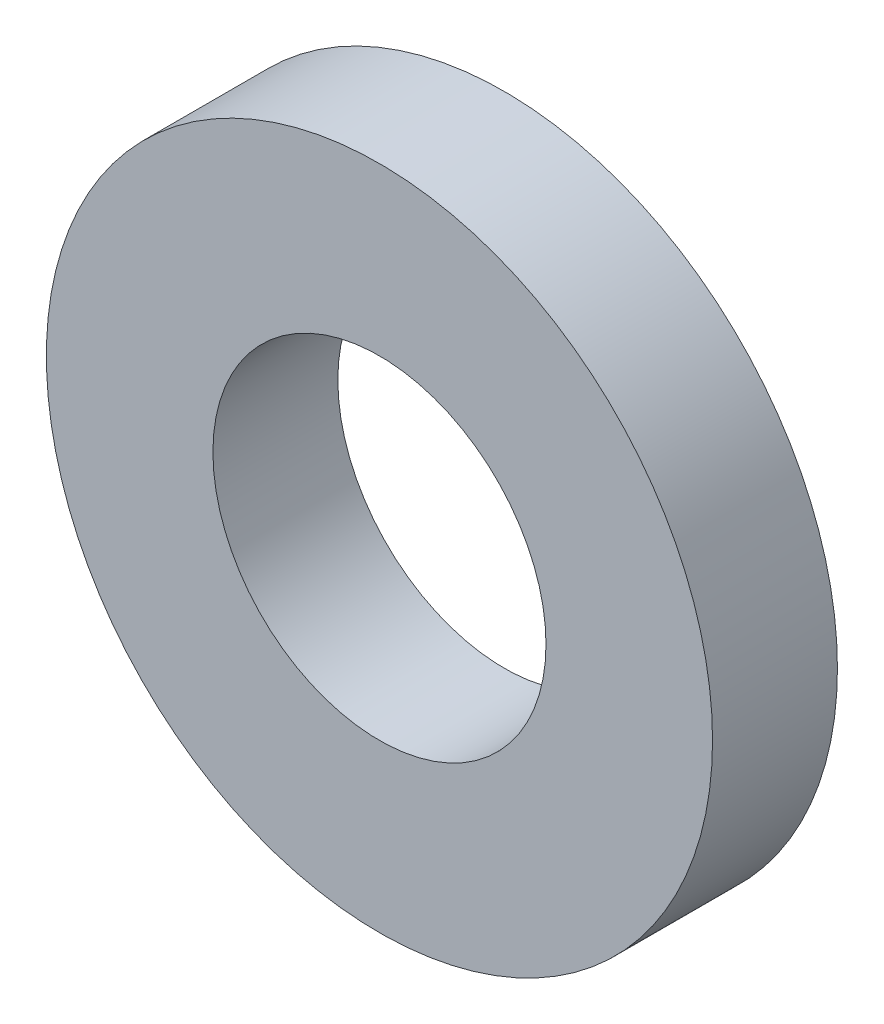
SolidWorks part; units mm, degrees
material "Nylon 101"
ref_plane "Front Plane" through (0, 0, 0) normal (0, 0, 1) x (1, 0, 0)
ref_plane "Top Plane" through (0, 0, 0) normal (0, 1, 0) x (1, 0, 0)
ref_plane "Right Plane" through (0, 0, 0) normal (1, 0, 0) x (0, 0, -1)
sketch "Sketch1" plane through (0, 0, 0) normal (0, 0, 1) x (1, 0, 0)
  circle A0 centre (0, 0) radius 6.35
  circle A1 centre (0, 0) radius 12.7
  dimension "D1" = 12.7
  dimension "D2" = 25.4
extrude "Boss-Extrude1" add sketch "Sketch1" along normal mid plane 4.7625
